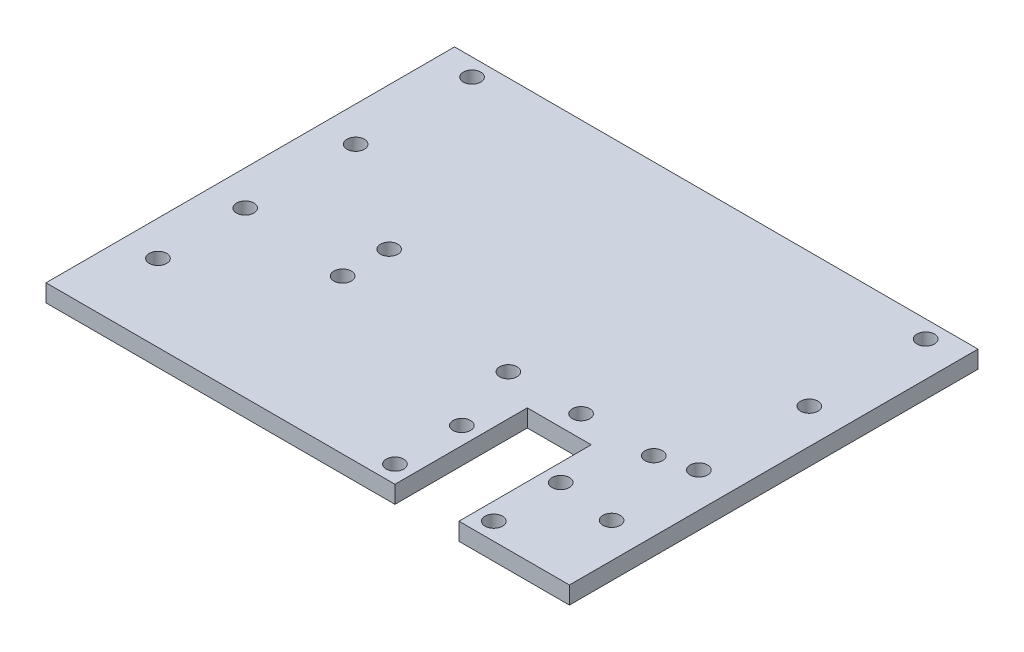
SolidWorks part; units mm, degrees
ref_plane "Front Plane" through (0, 0, 0) normal (0, 0, 1) x (1, 0, 0)
ref_plane "Top Plane" through (0, 0, 0) normal (0, 1, 0) x (1, 0, 0)
ref_plane "Right Plane" through (0, 0, 0) normal (1, 0, 0) x (0, 0, -1)
sketch "Sketch1" plane through (0, 0, 0) normal (0, 1, 0) x (1, 0, 0)
  line L1 (-45, -46.5) -> (45, -46.5)
  line L2 (-45, -46.5) -> (-45, 46.5)
  line L3 (-45, 46.5) -> (45, 46.5)
  line L4 (45, -46.5) -> (45, 46.5)
  line L5 (0, 46.5) -> (0, -46.5) construction
  line L6 (-45, 0) -> (45, 0) construction
  line L7 (26, -46.5) -> (15, -46.5)
  line L8 (26, -46.5) -> (26, -1)
  line L9 (26, -1) -> (15, -1)
  line L10 (15, -46.5) -> (15, -1)
  point P0 (0, 0)
  dimension "D1" = 90
  dimension "D2" = 93
  dimension "D3" = 19
  dimension "D4" = 30
  dimension "D5" = 45.5
extrude "Boss-Extrude1" add sketch "Sketch1" along normal blind 3 contours L1 L10 L9 L8 L4 L3 L2
sketch "Sketch2" plane through (0, 3, 0) normal (0, 1, 0) x (1, 0, 0)
  line L0 (-45, -46.5) -> (-45, 46.5) construction
  line L1 (45, -46.5) -> (45, 46.5) construction
  line L2 (-45, -46.5) -> (15, -46.5) construction
  line L3 (26, -46.5) -> (45, -46.5) construction
  circle A0 centre (39, 4.5) radius 1.5
  circle A1 centre (39, -10.5) radius 1.5
  circle A2 centre (-39, 4.5) radius 1.5
  circle A3 centre (-39, -10.5) radius 1.5
  dimension "D9" = 3
  dimension "D10" = 3
  dimension "D11" = 3
  dimension "D12" = 3
  dimension "D1" = 6
  dimension "D2" = 6
  dimension "D3" = 6
  dimension "D4" = 6
  dimension "D5" = 36
  dimension "D6" = 51
  dimension "D7" = 51
  dimension "D8" = 36
extrude "Cut-Extrude1" cut sketch "Sketch2" against normal through all
sketch "Sketch3" plane through (0, 3, 0) normal (0, 1, 0) x (1, 0, 0)
  line L0 (-45, -20.75) -> (45, -20.75) construction
  line L1 (-45, -46.5) -> (-45, 46.5) construction
  line L2 (45, -46.5) -> (45, 46.5) construction
  line L3 (-45, -46.5) -> (15, -46.5) construction
  line L4 (26, -46.5) -> (26, -1) construction
  line L5 (15, -46.5) -> (15, -1) construction
  circle A0 centre (29, -20.75) radius 1.5
  circle A1 centre (12, -20.75) radius 1.5
  dimension "D2" = 3
  dimension "D4" = 3
  dimension "D1" = 25.75
  dimension "D3" = 3
  dimension "D5" = 3
extrude "Cut-Extrude2" cut sketch "Sketch3" against normal through all
sketch "Sketch4" plane through (0, 3, 0) normal (0, 1, 0) x (1, 0, 0)
  line L0 (-45, -9.25) -> (45, -9.25) construction
  line L1 (-45, -46.5) -> (-45, 46.5) construction
  line L2 (45, -46.5) -> (45, 46.5) construction
  line L3 (-45, -20.75) -> (45, -20.75) construction
  line L4 (15, -46.5) -> (15, -1) construction
  line L5 (26, -46.5) -> (26, -1) construction
  circle A0 centre (12, -9.25) radius 1.5
  circle A1 centre (29, -9.25) radius 1.5
  dimension "D2" = 3
  dimension "D3" = 3
  dimension "D1" = 11.5
  dimension "D4" = 3
  dimension "D5" = 3
extrude "Cut-Extrude3" cut sketch "Sketch4" against normal through all
sketch "Sketch5" plane through (0, 3, 0) normal (0, 1, 0) x (1, 0, 0)
  line L0 (-45, -46.5) -> (-45, 46.5) construction
  line L1 (45, -46.5) -> (-45, -46.5)
  line L2 (45, -46.5) -> (45, -23.75)
  line L3 (45, -23.75) -> (-45, -23.75)
  line L4 (-45, -46.5) -> (-45, -23.75)
  line L5 (-45, -20.75) -> (45, -20.75) construction
  dimension "D1" = 3
extrude "Cut-Extrude4" cut sketch "Sketch5" against normal through all
sketch "Sketch6" plane through (0, 3, 0) normal (0, 1, 0) x (1, 0, 0)
  line L0 (-45, 2.75) -> (45, 2.75) construction
  line L1 (-45, -23.75) -> (-45, 46.5) construction
  line L2 (45, -23.75) -> (45, 46.5) construction
  line L3 (-45, -9.25) -> (45, -9.25) construction
  line L4 (20.5, -1) -> (20.5, 46.5) construction
  line L5 (26, -1) -> (15, -1) construction
  line L6 (-45, 46.5) -> (45, 46.5) construction
  circle A0 centre (20.5, 2.75) radius 1.5
  circle A1 centre (33, 2.75) radius 1.5
  circle A2 centre (8, 2.75) radius 1.5
  dimension "D2" = 3
  dimension "D4" = 3
  dimension "D1" = 12
  dimension "D3" = 12.5
extrude "Cut-Extrude5" cut sketch "Sketch6" against normal through all and the other way through all
sketch "Sketch7" plane through (0, 3, 0) normal (0, 1, 0) x (1, 0, 0)
  line L0 (-45, 23.5) -> (45, 23.5) construction
  line L1 (-45, -46.5) -> (-45, 46.5) construction
  line L2 (45, -46.5) -> (45, 46.5) construction
  line L3 (-45, -46.5) -> (45, -46.5) construction
  circle A0 centre (-39, 23.5) radius 1.5
  circle A1 centre (39, 23.5) radius 1.5
  dimension "D3" = 3
  dimension "D5" = 3
  dimension "D1" = 70
  dimension "D2" = 6
  dimension "D4" = 6
extrude "Cut-Extrude6" cut sketch "Sketch7" against normal through all
sketch "Sketch8" plane through (0, 3, 0) normal (0, 1, 0) x (1, 0, 0)
  line L0 (-45, 43.5) -> (45, 43.5) construction
  line L1 (-45, -46.5) -> (-45, 46.5) construction
  line L2 (45, -46.5) -> (45, 46.5) construction
  line L3 (-45, -46.5) -> (45, -46.5) construction
  circle A0 centre (-39, 43.5) radius 1.5
  circle A1 centre (39, 43.5) radius 1.5
  dimension "D3" = 3
  dimension "D5" = 3
  dimension "D1" = 90
  dimension "D2" = 6
  dimension "D4" = 6
extrude "Cut-Extrude7" cut sketch "Sketch8" against normal through all
sketch "Sketch9" plane through (0, 3, 0) normal (0, 1, 0) x (1, 0, 0)
  line L0 (16.5, 46.5) -> (16.5, -1) construction
  line L1 (-45, 46.5) -> (45, 46.5) construction
  line L2 (26, -1) -> (15, -1) construction
  line L3 (20.5, -1) -> (20.5, 46.5) construction
  line L4 (-13.5, 46.5) -> (-13.5, -23.75) construction
  line L5 (15, -23.75) -> (-45, -23.75) construction
  line L6 (-26.5, 46.5) -> (-26.5, -23.75) construction
  line L7 (-22.5, 46.5) -> (-22.5, -23.75) construction
  line L8 (-20.5, 46.5) -> (-20.5, -23.75) construction
  line L9 (-45, 2.75) -> (45, 2.75) construction
  circle A0 centre (-20.5, 2.75) radius 1.5
  circle A1 centre (-20.5, 10.75) radius 1.5
  dimension "D6" = 0
  dimension "D7" = 3
  dimension "D9" = 3
  dimension "D1" = 4
  dimension "D2" = 30
  dimension "D3" = 13
  dimension "D4" = 4
  dimension "D5" = 2
  dimension "D8" = 8
extrude "Cut-Extrude8" cut sketch "Sketch9" against normal through all
